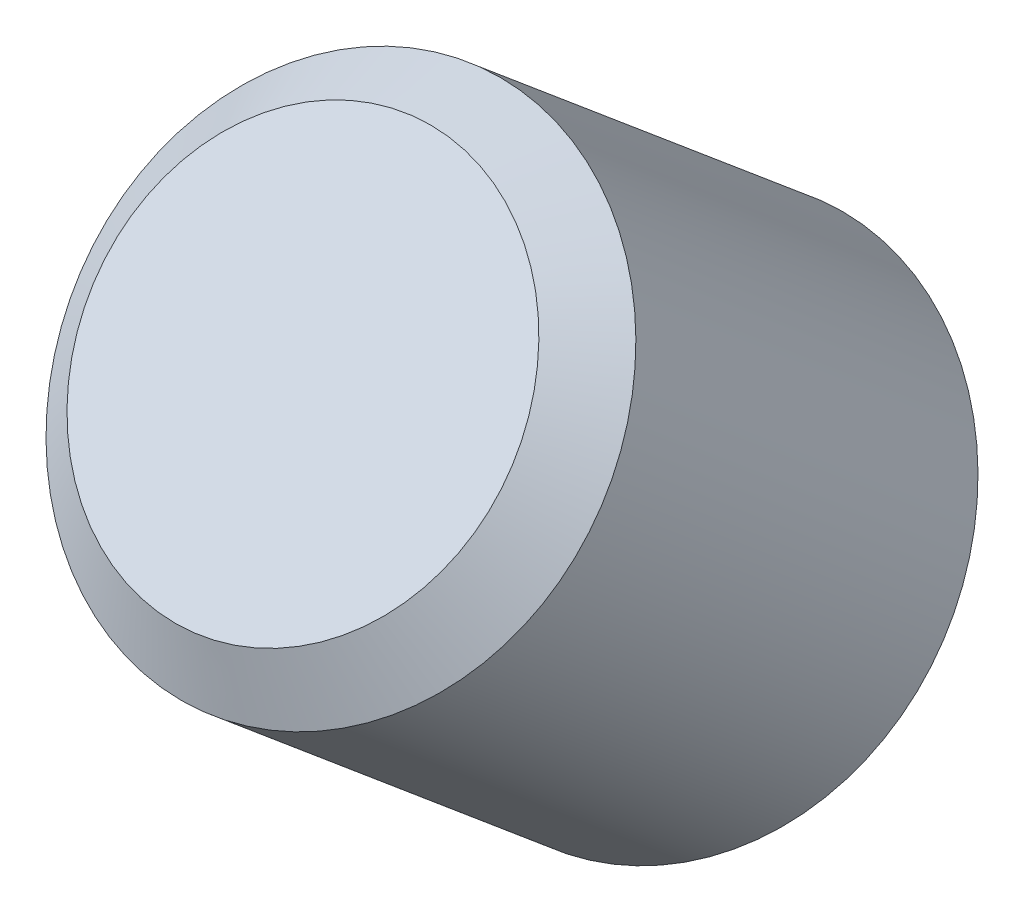
SolidWorks part; units mm, degrees
material "ABS"
ref_plane "Front Plane" through (0, 0, 0) normal (0, 0, 1) x (1, 0, 0)
ref_plane "Top Plane" through (0, 0, 0) normal (0, 1, 0) x (1, 0, 0)
ref_plane "Right Plane" through (0, 0, 0) normal (1, 0, 0) x (0, 0, -1)
sketch "Sketch2" plane through (0, 4.567, 5.4427) normal (0, 0.6428, 0.766) x (1, 0, 0)
  line L0 (38.684, 67.8158) -> (38.684, 73.012) construction
  line L1 (38.784, 67.7587) -> (38.784, 73.0691)
  line L2 (38.684, 67.8158) -> (38.684, 73.012) construction
  arc A0 (38.684, 73.012) -> (38.684, 67.8158) centre (37.184, 70.4139) ccw construction
  arc A2 (38.784, 73.0691) -> (38.784, 67.7587) centre (37.184, 70.4139) ccw
  circle A3 centre (37.184, 70.4139) radius 5
  point P5 (0, 0)
  point P8 (0, 0)
  point P12 (38.684, 67.8158)
  point P13 (0, 0)
  point P14 (37.184, 70.4139)
  point P16 (0, 0)
  point P17 (0, 0)
  point P18 (37.25, 70.7693)
  point P19 (37.25, 70.6366)
  dimension "D2" = 10
  dimension "D3" = 0.1
  dimension "D1" = 0.1
extrude "Boss-Extrude1" add sketch "Sketch2" along normal blind 10
sketch "Sketch3" plane through (0, 10.9949, 13.1032) normal (0, 0.6428, 0.766) x (1, 0, 0)
  circle A0 centre (37.184, 70.4139) radius 5
  circle A1 centre (37.184, 70.4139) radius 5 construction
  point P3 (37.25, 70.7693)
extrude "Boss-Extrude2" add sketch "Sketch3" along normal blind 1
chamfer "Chamfer1" distance 1 angle 45 2 edges at (37.184, 54.677, -36.6045) (37.184, 61.7476, -28.178)
